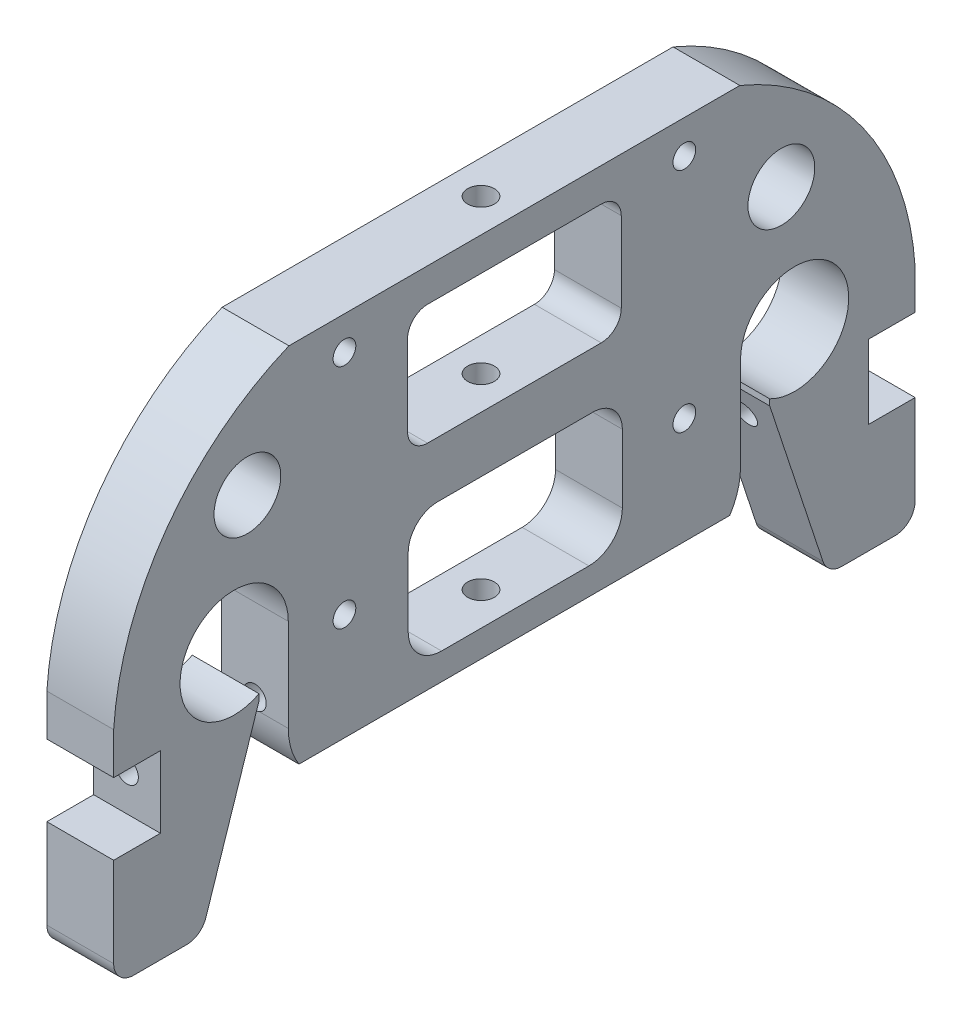
SolidWorks part; units mm, degrees
ref_plane "Спереди" through (0, 0, 0) normal (0, 0, 1) x (1, 0, 0)
ref_plane "Сверху" through (0, 0, 0) normal (0, 1, 0) x (1, 0, 0)
ref_plane "Справа" through (0, 0, 0) normal (1, 0, 0) x (0, 0, -1)
sketch "Эскиз1" plane through (0, 0, 0) normal (1, 0, 0) x (0, 0, -1)
  line L0 (3, 0) -> (10.9531, 0)
  line L1 (120, 3) -> (120, 67)
  line L2 (117, 70) -> (3, 70)
  line L3 (0, 67) -> (0, 3)
  line L4 (0, 0) -> (0, 34.4099)
  line L5 (42, 65) -> (34.556, 65)
  line L6 (21.7669, 26.2099) -> (13.8022, 2.0604)
  line L7 (21.7669, 26.2099) -> (21.7669, 27.1263)
  line L8 (26.1459, 34.3209) -> (26.1458, 20.4331)
  line L9 (60, -930) -> (60, 49070)
  line L10 (36.1458, 10.433) -> (83.8542, 10.433)
  line L11 (47, 65) -> (73, 65)
  line L12 (93.8541, 34.3209) -> (93.8542, 20.4331)
  line L13 (34.556, 65) -> (34.556, 31)
  line L14 (34.556, 31) -> (34.556, 65)
  line L15 (98.2331, 26.2099) -> (98.2331, 27.1263)
  line L16 (47, 47) -> (73, 47)
  line L17 (34.556, 65) -> (6, 65)
  line L18 (42, 65) -> (44, 65)
  line L19 (44, 62) -> (44, 50)
  line L20 (98.2331, 26.2099) -> (106.1978, 2.0604)
  line L21 (76, 62) -> (76, 50)
  line L22 (85.444, 65) -> (114, 65)
  line L23 (109.0469, 0) -> (117, 0)
  line L24 (48.5129, 34.2241) -> (71.7456, 34.2241) construction
  line L25 (48.5129, 38.6402) -> (71.7456, 38.6402)
  line L26 (48.5129, 29.808) -> (71.7456, 29.808)
  arc A0 (26.1459, 34.3209) -> (21.7669, 27.1263) centre (18.0459, 34.321) ccw
  circle A1 centre (34.556, 65) radius 1.7
  circle A3 centre (34.556, 31) radius 1.7
  arc A4 (93.8541, 34.3209) -> (98.2331, 27.1263) centre (101.9541, 34.321) cw
  circle A5 centre (85.444, 31) radius 1.7
  circle A6 centre (85.444, 65) radius 1.7
  arc A8 (26.1458, 20.4331) -> (36.1458, 10.433) centre (36.1458, 20.433) ccw
  arc A9 (93.8542, 20.4331) -> (83.8542, 10.433) centre (83.8542, 20.433) cw
  arc A10 (44, 62) -> (47, 65) centre (47, 62) cw
  arc A11 (76, 50) -> (73, 47) centre (73, 50) cw
  arc A12 (76, 62) -> (73, 65) centre (73, 62) ccw
  arc A13 (44, 50) -> (47, 47) centre (47, 50) ccw
  arc A14 (3, 70) -> (0, 67) centre (3, 67) ccw
  arc A15 (120, 3) -> (117, 0) centre (117, 3) cw
  arc A16 (0, 3) -> (3, 0) centre (3, 3) ccw
  arc A17 (120, 67) -> (117, 70) centre (117, 67) ccw
  arc A18 (106.1978, 2.0604) -> (109.0469, 0) centre (109.0469, 3) ccw
  arc A19 (13.8022, 2.0604) -> (10.9531, 0) centre (10.9531, 3) cw
  arc A20 (48.5129, 38.6402) -> (48.5129, 29.808) centre (48.5129, 34.2241) ccw
  arc A21 (71.7456, 29.808) -> (71.7456, 38.6402) centre (71.7456, 34.2241) ccw
  point P16 (60, 70)
  point P22 (60, 10.433)
  point P36 (60, 47)
  point P37 (60, 65)
  point P43 (26.1456, 10.433)
  point P46 (93.8544, 10.433)
  point P52 (76, 47)
  point P55 (76, 65)
  point P58 (44, 47)
  point P70 (106.8774, 0)
  point P73 (13.1226, 0)
  point P76 (60.1293, 34.2241)
  dimension "D1" = 10
  dimension "D2" = 3
  dimension "D3" = 3
  dimension "D4" = 3
  dimension "D5" = 3
extrude "Бобышка-Вытянуть1" add sketch "Эскиз1" along normal blind 10
sketch "Эскиз2" plane through (0, 70, 0) normal (0, 1, 0) x (1, 0, 0)
  line L0 (5, 120) -> (5, 60)
  line L1 (10, 120) -> (0, 120) construction
  line L2 (5, 60) -> (9.6374, 60)
  circle A0 centre (5, 60) radius 2
extrude "Вырез-Вытянуть1" cut sketch "Эскиз2" against normal blind 67 contours L0 A0 L2 | L2 A0 L0
sketch "Эскиз3" plane through (0, 0, 0) normal (-1, 0, 0) x (0, 0, 1)
  line L0 (-89.4771, 22) -> (-89.4771, 24.8977)
  line L1 (-59.9497, 44.0397) -> (-59.9497, 43.9951)
  line L2 (-89.4771, 22) -> (-89.4771, 19.1)
  line L3 (-62.852, 42.5321) -> (-62.852, 44.0397)
  line L5 (-62.852, 44.0397) -> (-57.0474, 44.0397)
  line L6 (-57.0474, 44.0397) -> (-57.0474, 41.0244)
  line L7 (-57.0474, 41.0244) -> (-62.852, 41.0244)
  line L8 (-62.852, 41.0244) -> (-62.852, 42.6301)
  line L11 (-89.4771, 22) -> (-87.9771, 22)
  line L12 (-87.9771, 22) -> (-87.9771, 24.8926)
  line L13 (-87.9771, 24.8926) -> (-87.9771, 19.0972)
  line L14 (-87.9771, 19.0972) -> (-90.9771, 19.0972)
  line L15 (-90.9771, 19.0972) -> (-90.9771, 24.8926)
  line L16 (-90.9771, 24.8926) -> (-87.9771, 24.8926)
  line L18 (-32.0229, 24.8922) -> (-32.0229, 19.099)
  line L19 (-32.0229, 19.099) -> (-29.0229, 19.099)
  line L20 (-29.0229, 24.8922) -> (-32.0229, 24.8922)
  line L21 (-29.0229, 19.099) -> (-29.0229, 24.8922)
  point P14 (-59.9497, 42.5321)
  point P21 (-30.5229, 21.9956)
extrude "Вырез-Вытянуть2" cut sketch "Эскиз3" against normal blind 8
sketch "Эскиз5" plane through (0, 0, -120) normal (0, 0, -1) x (-1, 0, 0)
  line L0 (-5, 70) -> (-5, 22)
  line L1 (-10, 70) -> (0, 70) construction
  circle A0 centre (-5, 22) radius 1.7
extrude "Вырез-Вытянуть3" cut sketch "Эскиз5" against normal blind 31
sketch "Эскиз6" plane through (0, 0, 0) normal (0, 0, 1) x (1, 0, 0)
  line L0 (5, 70) -> (5, 22)
  line L1 (10, 70) -> (0, 70) construction
  circle A0 centre (5, 22) radius 1.7
extrude "Вырез-Вытянуть4" cut sketch "Эскиз6" against normal blind 31
sketch "Эскиз7" plane through (0, 0, 0) normal (-1, 0, 0) x (0, 0, 1)
  line L0 (-76.1617, 34.2241) -> (-83.8542, 10.433)
  line L1 (-83.8542, 10.433) -> (-36.1458, 10.433)
  line L2 (-36.1458, 10.433) -> (-44.0968, 34.2241)
  line L3 (-76.1617, 34.2241) -> (-44.0968, 34.2241)
  line L4 (-83.8542, 70) -> (-83.8542, 19)
  line L5 (-117, 70) -> (-3, 70) construction
  line L7 (-83.8542, 19) -> (-44.0968, 19)
  line L8 (-44.0968, 19) -> (-44.0968, 34.2241)
  line L9 (-76.1617, 34.2241) -> (-76.1617, 19)
  arc A0 (-71.7456, 38.6402) -> (-71.7456, 29.808) centre (-71.7456, 34.2241) ccw construction
  arc A1 (-48.5129, 29.808) -> (-48.5129, 38.6402) centre (-48.5129, 34.2241) ccw construction
  arc M45 (-48.5129, 38.6402) -> (-48.5129, 29.808) centre (-48.5129, 34.2241) cw
  line M46 (-48.5129, 29.808) -> (-71.7456, 29.808)
  arc M47 (-71.7456, 29.808) -> (-71.7456, 38.6402) centre (-71.7456, 34.2241) cw
sketch "Эскиз9" plane through (0, 0, 0) normal (-1, 0, 0) x (0, 0, 1)
  line L0 (-60, 70) -> (-60, 31.9679)
  line L1 (-117, 70) -> (-3, 70) construction
  circle A0 centre (-99.974, 53.7494) radius 5
  circle A1 centre (-20.026, 53.7494) radius 5
extrude "Вырез-Вытянуть6" cut sketch "Эскиз9" against normal blind 10 contours A0 | A1
extrude "Вырез-Вытянуть7" cut sketch "Эскиз7" against normal blind 10 contours L9 L7 L8 M47 M45 M46
sketch "Эскиз10" plane through (0, 0, 0) normal (-1, 0, 0) x (0, 0, 1)
  line L0 (-60.1293, 19) -> (-60.1293, 15)
  line L1 (-76.1617, 19) -> (-44.0968, 19) construction
  line L2 (-60.1293, 15) -> (-92.2496, 15)
  line L3 (-92.2496, 15) -> (-26.8208, 15)
  line L4 (-26.8208, 15) -> (-26.8208, 8.6256)
  line L5 (-26.8208, 8.6256) -> (-93.1657, 8.6256)
  line L6 (-93.1657, 8.6256) -> (-93.1657, 15)
  line L7 (-93.1657, 15) -> (-92.2496, 15)
  line L8 (-1060.1293, 19) -> (48939.8707, 19)
  line L9 (-1060.1293, 15) -> (48939.8707, 15)
  arc A0 (-93.8542, 20.4331) -> (-83.8542, 10.433) centre (-83.8542, 20.433) ccw construction
extrude "Вырез-Вытянуть9" cut sketch "Эскиз10" against normal blind 10 contours L7 L6 L5 L4 L3 L2
fillet "Скругление1" radius 5 2 edges at (5, 19, -44.0968) (5, 19, -76.1617)
sketch "Эскиз11" plane through (0, 0, 0) normal (-1, 0, 0) x (0, 0, 1)
  line L1 (-117, 70) -> (-3, 70) construction
  line L2 (-93.7561, 70) -> (-80.9232, 70)
  line L3 (-80.9232, 70) -> (-105.6625, 70)
  line L4 (-105.6625, 70) -> (-120.0923, 70)
  line L5 (-120.0923, 70) -> (-120.0305, 30.5452)
  line L7 (-120.0904, 30.1404) -> (-120.0923, 30.5452)
  line L8 (-120.0923, 30.5452) -> (-108.8732, 30.5452)
  line L9 (0.0923, 70) -> (0.0305, 30.5452)
  line L10 (-14.3375, 70) -> (0.0923, 70)
  line L11 (-39.0768, 70) -> (-14.3375, 70)
  arc A0 (-93.7561, 70) -> (-120.0904, 30.1404) centre (-77.3702, 30.5452) ccw
  arc A1 (-26.2439, 70) -> (0.0904, 30.1404) centre (-42.6298, 30.5452) cw
extrude "Вырез-Вытянуть10" cut sketch "Эскиз11" against normal blind 10 and the other way through all contours A0 L3 L4 L5 | L11 A1 L9 L10
sketch "Эскиз12" plane through (0, 0, -120) normal (0, 0, -1) x (-1, 0, 0)
  line L0 (-10, 3) -> (-10, 33.3517) construction
  line L1 (-10, 27.4626) -> (0, 27.4626)
  line L2 (-10, 27.4626) -> (-10, 16.4138)
  line L3 (-10, 16.4138) -> (0, 16.4138)
  line L4 (0, 27.4626) -> (0, 16.4138)
  line L5 (0, 3) -> (0, 33.3517) construction
extrude "Вырез-Вытянуть11" cut sketch "Эскиз12" against normal blind 7
sketch "Эскиз14" plane through (0, 0, 0) normal (0, 0, 1) x (1, 0, 0)
  line L1 (0, 27.1263) -> (10, 27.1263)
  line L2 (0, 27.1263) -> (0, 16.4138)
  line L3 (0, 16.4138) -> (10, 16.4138)
  line L4 (10, 27.1263) -> (10, 16.4138)
extrude "Вырез-Вытянуть12" cut sketch "Эскиз14" against normal blind 7
